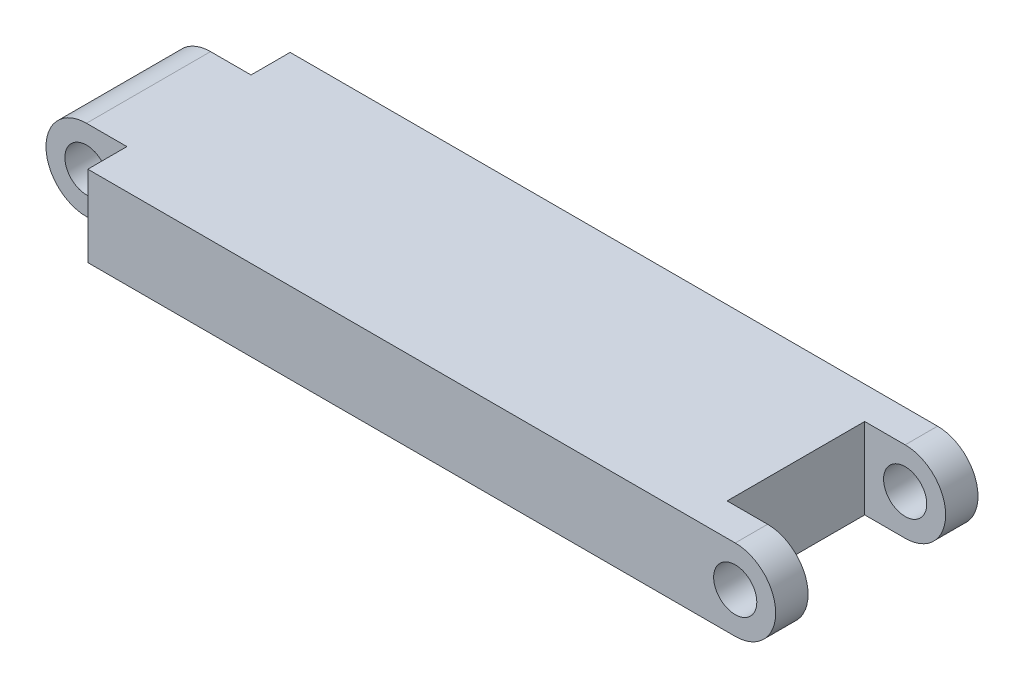
SolidWorks part; units mm, degrees
ref_plane "前视基准面" through (0, 0, 0) normal (0, 0, 1) x (1, 0, 0)
ref_plane "上视基准面" through (0, 0, 0) normal (0, 1, 0) x (1, 0, 0)
ref_plane "右视基准面" through (0, 0, 0) normal (1, 0, 0) x (0, 0, -1)
sketch "草图1" plane through (0, 0, 0) normal (0, 1, 0) x (1, 0, 0)
  line L1 (-23.2474, 10.8942) -> (33.7526, 10.8942)
  line L2 (-23.2474, 10.8942) -> (-23.2474, -4.1058)
  line L3 (-23.2474, -4.1058) -> (33.7526, -4.1058)
  line L4 (33.7526, 10.8942) -> (33.7526, -4.1058)
  dimension "D1" = 57
  dimension "D2" = 15
extrude "凸台-拉伸5" add sketch "草图1" along normal blind 6
sketch "草图13" plane through (0, 6, 0) normal (0, 1, 0) x (1, 0, 0)
  line L0 (33.7526, -4.1058) -> (33.7526, 10.8942) construction
  line L1 (27.7526, 8.4942) -> (33.7526, 8.4942)
  line L2 (27.7526, 8.4942) -> (27.7526, -1.7058)
  line L3 (27.7526, -1.7058) -> (33.7526, -1.7058)
  line L4 (33.7526, 8.4942) -> (33.7526, -1.7058)
  line L5 (33.7526, 10.8942) -> (-23.2474, 10.8942) construction
  point P4 (33.7526, 3.3942)
  point P5 (33.7526, 3.3942)
  dimension "D1" = 6
  dimension "D2" = 2.4
extrude "切除-拉伸8" cut sketch "草图13" against normal blind 6
sketch "草图14" plane through (0, 0, 4.1058) normal (0, 0, 1) x (1, 0, 0)
  line L0 (-23.2474, 0) -> (33.7526, 0) construction
  line L1 (33.7526, 6) -> (27.7526, 6) construction
  line L2 (33.7526, 6) -> (33.7526, 0) construction
  line L3 (33.7526, 0) -> (27.7526, 0) construction
  line L4 (27.7526, 6) -> (27.7526, 0) construction
  line L5 (30.7526, 6) -> (33.7526, 6)
  line L6 (33.7526, 6) -> (33.7526, 0)
  line L7 (33.7526, 0) -> (30.7526, 0)
  arc A0 (30.7526, 6) -> (30.7526, 0) centre (30.7526, 3) cw
  circle A1 centre (30.7526, 3) radius 1.6
  point P7 (33.7526, 3)
  point P8 (30.7526, 6)
  point P9 (27.7526, 3)
  point P10 (30.7526, 0)
  line M2 (-23.2474, 0) -> (33.7526, 0)
  line M3 (33.7526, 0) -> (33.7526, 6)
  line M4 (33.7526, 6) -> (-23.2474, 6)
  dimension "D1" = 6
extrude "切除-拉伸9" cut sketch "草图14" against normal blind 17 contours A1 | A0 L6 M4 | A0 M3 M2
sketch "草图15" plane through (0, 6, 0) normal (0, 1, 0) x (1, 0, 0)
  line L1 (-23.2474, 10.8942) -> (-17.2474, 10.8942)
  line L2 (-23.2474, 10.8942) -> (-23.2474, 8.4942)
  line L3 (-23.2474, 8.4942) -> (-17.2474, 8.4942)
  line L4 (-17.2474, 10.8942) -> (-17.2474, 8.4942)
  line L5 (-23.2474, -4.1058) -> (-17.2474, -4.1058)
  line L6 (-23.2474, -4.1058) -> (-23.2474, -1.7058)
  line L7 (-23.2474, -1.7058) -> (-17.2474, -1.7058)
  line L8 (-17.2474, -4.1058) -> (-17.2474, -1.7058)
  line L9 (30.7526, 8.4942) -> (27.7526, 8.4942) construction
  line L10 (27.7526, -1.7058) -> (30.7526, -1.7058) construction
  dimension "D1" = 6
extrude "切除-拉伸10" cut sketch "草图15" against normal blind 17
sketch "草图16" plane through (0, 0, 1.7058) normal (0, 0, 1) x (1, 0, 0)
  line L0 (-23.2474, 0) -> (-23.2474, 6) construction
  line L1 (-17.2474, 0) -> (-23.2474, 0) construction
  line L2 (-17.2474, 6) -> (-23.2474, 6) construction
  line L3 (-17.2474, 0) -> (-17.2474, 6) construction
  line L4 (-20.2474, 6) -> (-23.2474, 6)
  line L5 (-23.2474, 6) -> (-23.2474, 0)
  line L6 (-23.2474, 0) -> (-20.2474, 0)
  arc A0 (-20.2474, 0) -> (-20.2474, 6) centre (-20.2474, 3) cw
  circle A1 centre (-20.2474, 3) radius 1.6
  point P0 (-23.2474, 3)
  point P1 (-20.2474, 0)
  point P4 (-20.2474, 6)
  point P7 (-17.2474, 3)
  line M2 (-17.2474, 6) -> (-23.2474, 6)
  line M3 (-23.2474, 6) -> (-23.2474, 0)
  line M4 (-23.2474, 0) -> (-17.2474, 0)
extrude "切除-拉伸11" cut sketch "草图16" against normal blind 17 contours A1 | A0 M3 M2 | A0 L5 M4
sketch "草图17" plane through (0, 0, -8.4942) normal (0, 0, -1) x (-1, 0, 0)
  line L0 (20.2474, 0) -> (17.2474, 0) construction
  line L1 (17.2474, 6) -> (23.2474, 6)
  line L2 (17.2474, 6) -> (17.2474, 0)
  line L3 (17.2474, 0) -> (23.2474, 0)
  line L4 (23.2474, 6) -> (23.2474, 0)
  line L5 (17.2474, 6) -> (23.2474, 0) construction
  line L6 (17.2474, 0) -> (23.2474, 6) construction
  arc A0 (20.2474, 0) -> (20.2474, 6) centre (20.2474, 3) ccw construction
  point P4 (20.2474, 3)
extrude "切除-拉伸12" cut sketch "草图17" against normal blind 0.5
sketch "草图18" plane through (0, 0, 1.7058) normal (0, 0, 1) x (1, 0, 0)
  line L0 (-17.2474, 0) -> (-20.2474, 0) construction
  line L1 (-17.2474, 6) -> (-23.2474, 6)
  line L2 (-17.2474, 6) -> (-17.2474, 0)
  line L3 (-17.2474, 0) -> (-23.2474, 0)
  line L4 (-23.2474, 6) -> (-23.2474, 0)
  line L5 (-17.2474, 6) -> (-23.2474, 0) construction
  line L6 (-17.2474, 0) -> (-23.2474, 6) construction
  arc A0 (-20.2474, 6) -> (-20.2474, 0) centre (-20.2474, 3) ccw construction
  point P4 (-20.2474, 3)
extrude "切除-拉伸13" cut sketch "草图18" against normal blind 0.5
